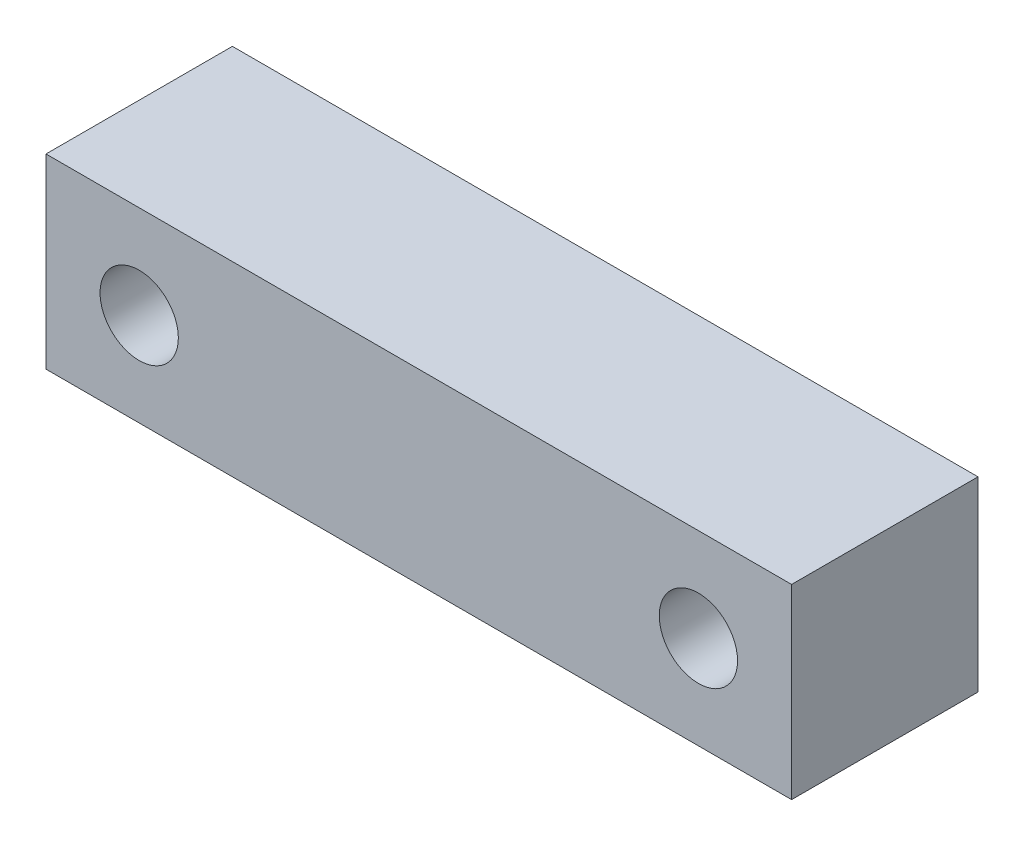
SolidWorks part; units mm, degrees
ref_plane "Front Plane" through (0, 0, 0) normal (0, 0, 1) x (1, 0, 0)
ref_plane "Top Plane" through (0, 0, 0) normal (0, 1, 0) x (1, 0, 0)
ref_plane "Right Plane" through (0, 0, 0) normal (1, 0, 0) x (0, 0, -1)
sketch "Sketch1" plane through (0, 0, 0) normal (0, 0, 1) x (1, 0, 0)
  line L0 (-15, 5) -> (-15, -5) construction
  line L1 (-20, -5) -> (20, -5)
  line L2 (-20, -5) -> (-20, 5)
  line L3 (-20, 5) -> (20, 5)
  line L4 (20, -5) -> (20, 5)
  line L5 (-20, -5) -> (20, 5) construction
  line L6 (-20, 5) -> (20, -5) construction
  line L7 (15, 5) -> (15, -5) construction
  circle A0 centre (-15, 0) radius 2.1
  circle A1 centre (15, 0) radius 2.1
  point P0 (0, 0)
  dimension "D1" = 40
  dimension "D5" = 4.2
  dimension "D2" = 10
  dimension "D3" = 5
  dimension "D4" = 5
extrude "Boss-Extrude1" add sketch "Sketch1" along normal blind 10
